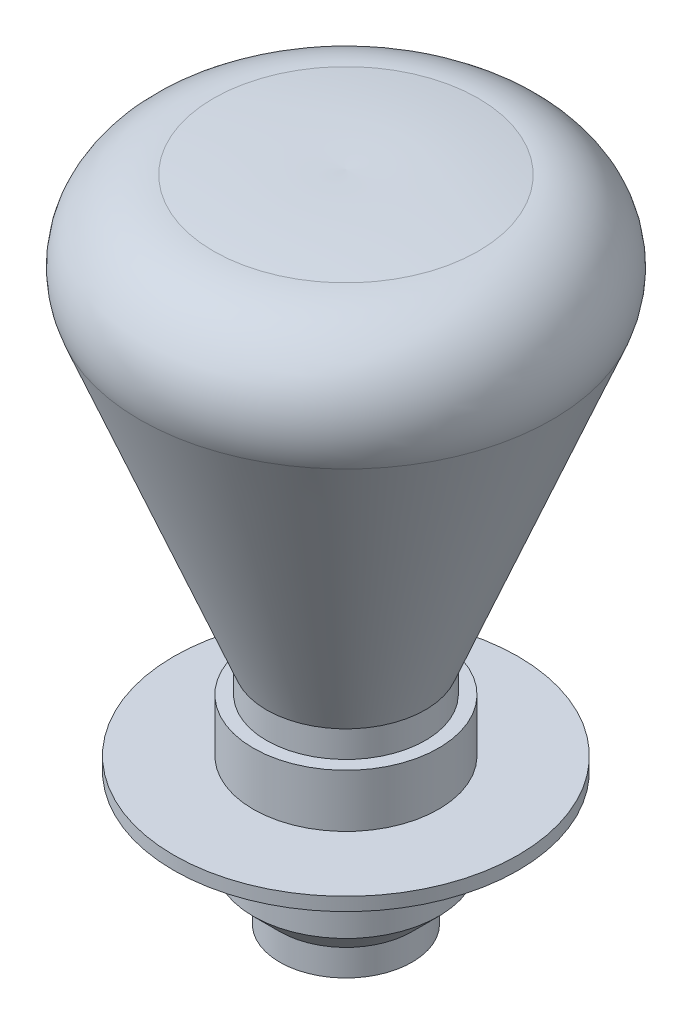
SolidWorks part; units mm, degrees
ref_plane "Front Plane" through (0, 0, 0) normal (0, 0, 1) x (1, 0, 0)
ref_plane "Top Plane" through (0, 0, 0) normal (0, 1, 0) x (1, 0, 0)
ref_plane "Right Plane" through (0, 0, 0) normal (1, 0, 0) x (0, 0, -1)
sketch "Sketch1" plane through (0, 0, 0) normal (0, 0, 1) x (1, 0, 0)
  line L0 (1.5, 32.4036) -> (1.5, -7.4318) construction
  line L1 (-1.5, 7.161) -> (-6.2829, 19.0406)
  line L4 (-1, -1.339) -> (1.5, -1.339)
  line L7 (-1, -0.339) -> (-1, -1.339)
  line L17 (-2, 0.661) -> (-2, 3.661)
  line L20 (-5, 3.661) -> (-2, 3.661)
  line L21 (-5, 3.661) -> (-5, 4.161)
  line L22 (-5, 4.161) -> (-2, 4.161)
  line L25 (-2, 4.161) -> (-2, 6.161)
  line L26 (-2, 6.161) -> (-1.5, 6.161)
  line L29 (-1.5, 6.161) -> (-1.5, 7.161)
  line L30 (-1.5, 7.161) -> (1.5, 7.161)
  line L32 (-3.5, 23.161) -> (0, 23.161)
  line L39 (-1, -0.339) -> (-2, 0.661)
  arc A0 (-3.5, 23.161) -> (3.5, 23.161) centre (0, -4.6597) cw
  arc A1 (-6.2829, 19.0406) -> (-3.5, 23.161) centre (-3.5, 20.161) cw
  point P3 (0, -16.1584)
  dimension "D2" = 3
  dimension "D3" = 2.5
  dimension "D12" = 28.04
  dimension "D5" = 3
  dimension "D6" = 3
  dimension "D8" = 0.5
  dimension "D14" = 2
  dimension "D16" = 1
revolve "Revolve1" add sketch "Sketch1" angle 360 about L0
